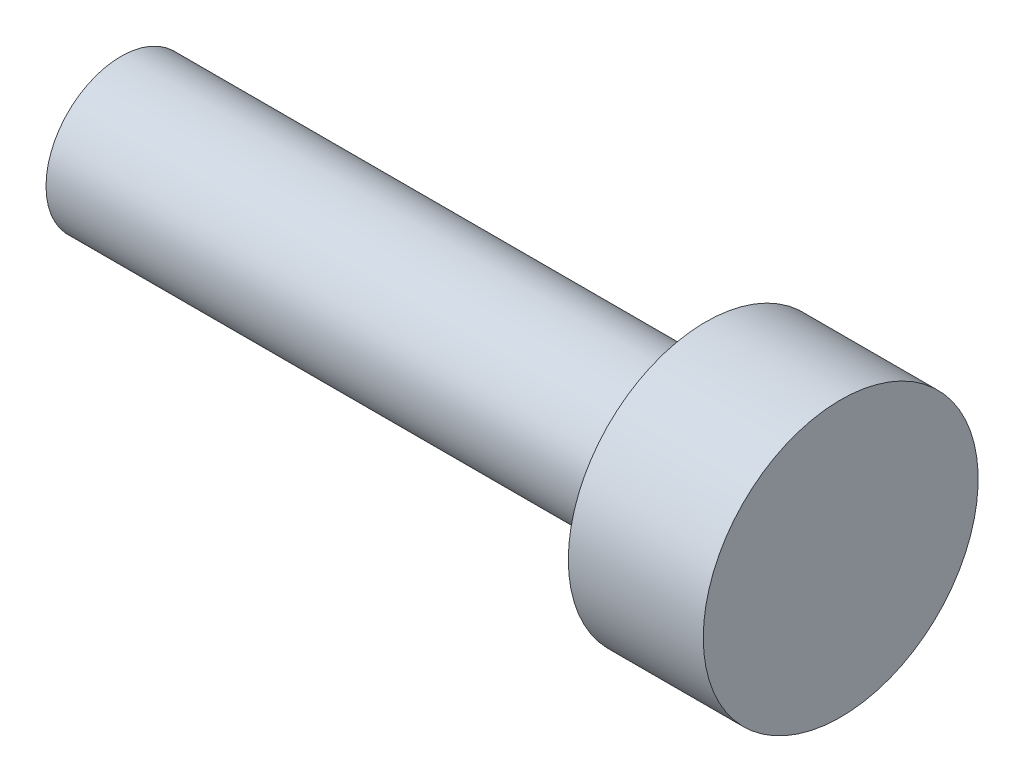
SolidWorks part; units mm, degrees
ref_plane "Front Plane" through (0, 0, 0) normal (0, 0, 1) x (1, 0, 0)
ref_plane "Top Plane" through (0, 0, 0) normal (0, 1, 0) x (1, 0, 0)
ref_plane "Right Plane" through (0, 0, 0) normal (1, 0, 0) x (0, 0, -1)
sketch "Axial profile (mm)" plane through (0, 0, 0) normal (0, 0, 1) x (1, 0, 0)
  line L0 (-110, 0) -> (75, 0) construction
  line L1 (165, 0) -> (179.4, 0)
  line L2 (179.4, 0) -> (179.4, 2.75)
  line L3 (179.4, 2.75) -> (176.7, 2.75)
  line L4 (176.7, 2.75) -> (176.7, 1.5)
  line L5 (176.7, 1.5) -> (165, 1.5)
  line L6 (165, 1.5) -> (165, 0)
revolve "Full revolution" add sketch "Axial profile (mm)" angle 360 about L0
